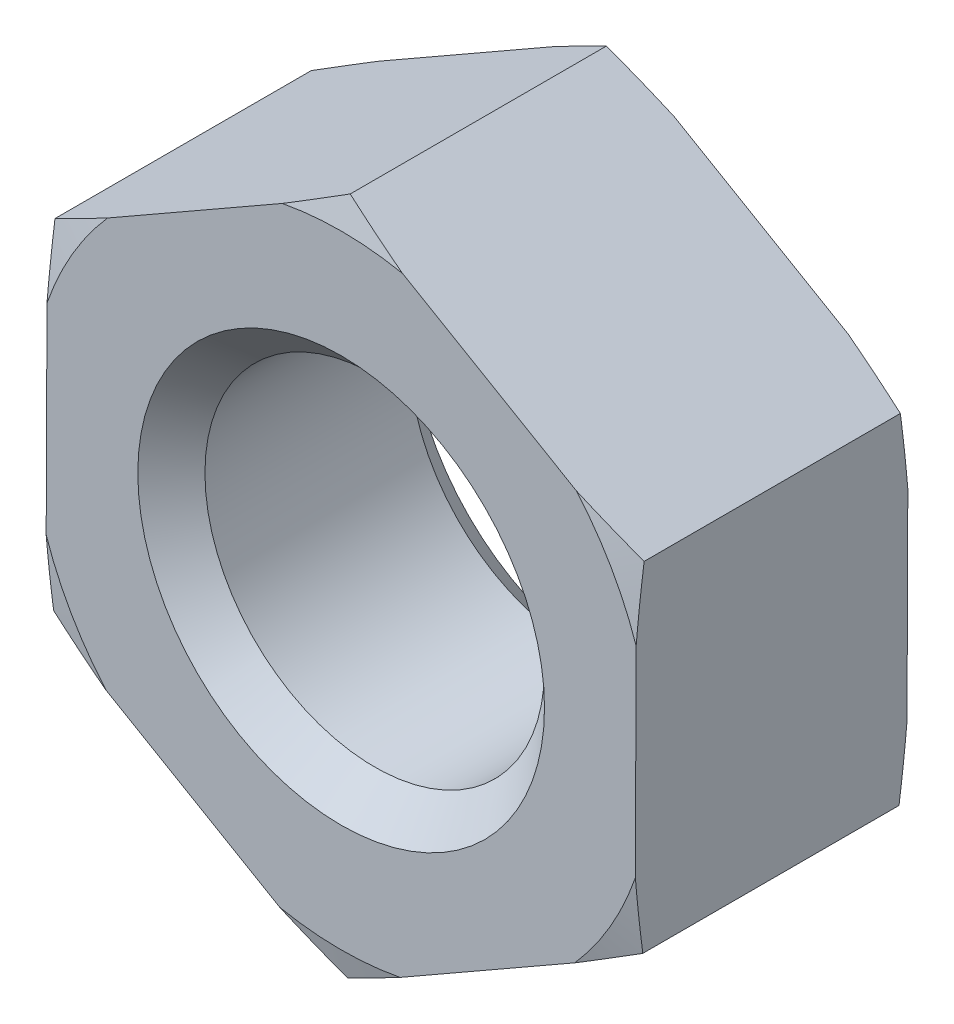
SolidWorks part; units mm, degrees
material "标准件"
ref_plane "基准面1" through (0, 0, 0) normal (0, 0, 1) x (1, 0, 0)
ref_plane "基准面2" through (0, 0, 0) normal (0, 1, 0) x (1, 0, 0)
ref_plane "基准面3" through (0, 0, 0) normal (1, 0, 0) x (0, 0, -1)
sketch "尺寸草图" plane through (0, 0, 0) normal (0, 0, 1) x (1, 0, 0)
  line L0 (0, 0) -> (33.9749, 0)
  line L1 (33.9749, 0) -> (37.4249, 0)
  line L2 (37.4249, 0) -> (42.0249, 0)
  line L3 (-2.8571, 0) -> (0, 0)
  point P3 (3, 0)
  point P4 (1.5, 0)
  point P5 (6.01, 0)
  point P6 (2.4, 0)
  point P7 (6.4, 0)
  point P8 (5.5, 0)
  dimension "D1" = 2.8571
  dimension "D" = 3
  dimension "P" = 1.5
  dimension "e" = 6.01
  dimension "m" = 2.4
  dimension "mw" = 6.4
  dimension "s" = 5.5
  dimension "da" = 3.45
  dimension "dw" = 4.6
sketch "草图1" plane through (0, 0, 0) normal (0, 0, 1) x (1, 0, 0)
  line L0 (-26.8088, 0) -> (37.1748, 0) construction
  line L1 (0, 25.0215) -> (0, -25.0215) construction
  line L3 (0.0118, 3.005) -> (-2.5965, 1.5127)
  line L4 (-2.5965, 1.5127) -> (-2.6083, -1.4923)
  line L5 (-2.6083, -1.4923) -> (-0.0118, -3.005)
  line L6 (-0.0118, -3.005) -> (2.5965, -1.5127)
  line L7 (2.5965, -1.5127) -> (2.6083, 1.4923)
  line L8 (2.6083, 1.4923) -> (0.0118, 3.005)
  circle A0 centre (0, 0) radius 2.6024 construction
  circle A1 centre (0, 0) radius 1.5
  dimension "D" = 3
  dimension "e" = 6.01
extrude "基体-拉伸" add sketch "草图1" along normal blind 2.4
cosmetic thread "装饰螺纹线1"
chamfer "倒角1" distance 0.2964 angle 45 2 edges at (1.5, 0, 0) (1.5, 0, 2.4)
sketch "草图2" plane through (0, 0, 0) normal (0, 0, -1) x (-1, 0, 0)
  circle A0 centre (0, 0) radius 2.75
  circle A1 centre (0, 0) radius 1.5 construction
  dimension "s" = 5.5
extrude "切除-拉伸1" cut sketch "草图2" against normal through all draft 75 flip side to cut
sketch "草图3" plane through (0, 0, 2.4) normal (0, 0, 1) x (1, 0, 0)
  circle A0 centre (0, 0) radius 2.75
  dimension "D1" = 5.5
extrude "切除-拉伸2" cut sketch "草图3" against normal through all draft 75 flip side to cut
